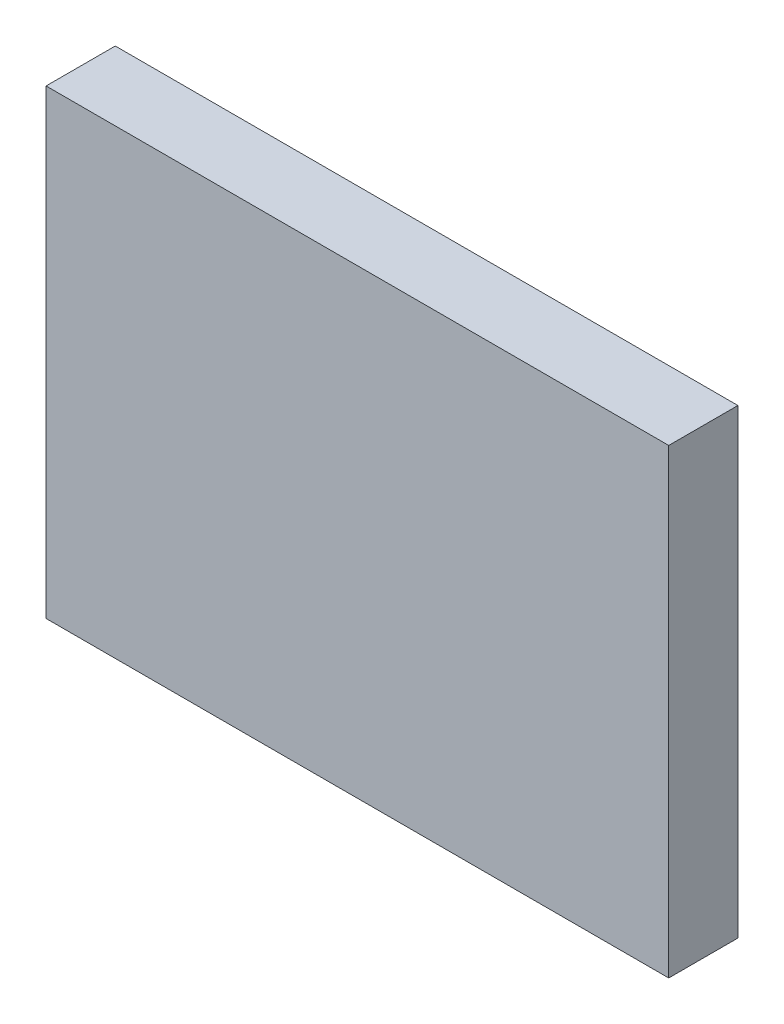
SolidWorks part; units mm, degrees
ref_plane "Front" through (0, 0, 0) normal (0, 0, 1) x (1, 0, 0)
ref_plane "Top" through (0, 0, 0) normal (0, 1, 0) x (1, 0, 0)
ref_plane "Right" through (0, 0, 0) normal (1, 0, 0) x (0, 0, -1)
sketch "Sketch1" plane through (0, 0, 0) normal (0, 0, 1) x (1, 0, 0)
  line L1 (-85.725, -63.5) -> (85.725, -63.5)
  line L2 (-85.725, -63.5) -> (-85.725, 63.5)
  line L3 (-85.725, 63.5) -> (85.725, 63.5)
  line L4 (85.725, -63.5) -> (85.725, 63.5)
  line L5 (-85.725, -63.5) -> (85.725, 63.5) construction
  line L6 (-85.725, 63.5) -> (85.725, -63.5) construction
  point P0 (0, 0)
  point P6 (0, 0)
  dimension "D1" = 127
  dimension "D2" = 171.45
extrude "Boss-Extrude1" add sketch "Sketch1" along normal mid plane 19.05 contours L3 L4 L1 L2
